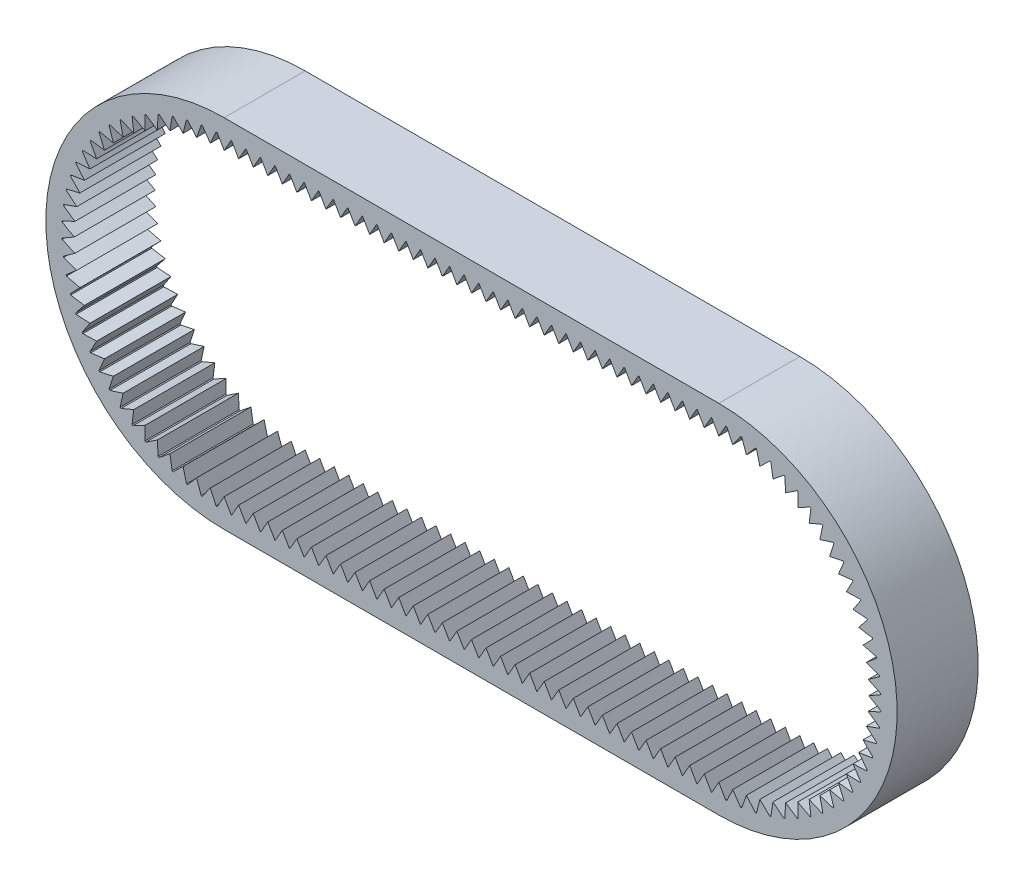
SolidWorks part; units mm, degrees
ref_plane "Front Plane" through (0, 0, 0) normal (0, 0, 1) x (1, 0, 0)
ref_plane "Top Plane" through (0, 0, 0) normal (0, 1, 0) x (1, 0, 0)
ref_plane "Right Plane" through (0, 0, 0) normal (1, 0, 0) x (0, 0, -1)
sketch "Sketch1" plane through (0, 0, 0) normal (0, 0, 1) x (1, 0, 0)
  line L0 (0.433, 10) -> (0.4646, 10)
  line L1 (0, 11) -> (30.5183, 11)
  line L2 (0, 9.25) -> (0.433, 10)
  line L4 (-0.4277, 9.9908) -> (0, 9.25)
  line L5 (30.0853, -10) -> (30.5183, -9.25)
  line L6 (0.8976, 9.25) -> (1.3306, 10)
  line L8 (0.4646, 10) -> (0.8976, 9.25)
  line L9 (1.7952, 9.25) -> (2.2282, 10)
  line L11 (1.3622, 10) -> (1.7952, 9.25)
  line L12 (2.6928, 9.25) -> (3.1258, 10)
  line L14 (2.2598, 10) -> (2.6928, 9.25)
  line L15 (3.5904, 9.25) -> (4.0234, 10)
  line L17 (3.1574, 10) -> (3.5904, 9.25)
  line L18 (4.488, 9.25) -> (4.921, 10)
  line L20 (4.055, 10) -> (4.488, 9.25)
  line L21 (5.3856, 9.25) -> (5.8186, 10)
  line L23 (4.9526, 10) -> (5.3856, 9.25)
  line L24 (6.2832, 9.25) -> (6.7162, 10)
  line L26 (5.8502, 10) -> (6.2832, 9.25)
  line L27 (7.1808, 9.25) -> (7.6138, 10)
  line L29 (6.7478, 10) -> (7.1808, 9.25)
  line L30 (8.0784, 9.25) -> (8.5114, 10)
  line L32 (7.6454, 10) -> (8.0784, 9.25)
  line L33 (8.976, 9.25) -> (9.409, 10)
  line L35 (8.543, 10) -> (8.976, 9.25)
  line L36 (9.8736, 9.25) -> (10.3066, 10)
  line L38 (9.4406, 10) -> (9.8736, 9.25)
  line L39 (10.7712, 9.25) -> (11.2042, 10)
  line L41 (10.3382, 10) -> (10.7712, 9.25)
  line L42 (11.6688, 9.25) -> (12.1018, 10)
  line L44 (11.2357, 10) -> (11.6688, 9.25)
  line L45 (12.5664, 9.25) -> (12.9994, 10)
  line L47 (12.1333, 10) -> (12.5664, 9.25)
  line L48 (13.464, 9.25) -> (13.897, 10)
  line L50 (13.0309, 10) -> (13.464, 9.25)
  line L51 (14.3616, 9.25) -> (14.7946, 10)
  line L53 (13.9285, 10) -> (14.3616, 9.25)
  line L54 (15.2591, 9.25) -> (15.6922, 10)
  line L56 (14.8261, 10) -> (15.2591, 9.25)
  line L57 (16.1567, 9.25) -> (16.5898, 10)
  line L59 (15.7237, 10) -> (16.1567, 9.25)
  line L60 (17.0543, 9.25) -> (17.4874, 10)
  line L62 (16.6213, 10) -> (17.0543, 9.25)
  line L63 (17.9519, 9.25) -> (18.385, 10)
  line L65 (17.5189, 10) -> (17.9519, 9.25)
  line L66 (18.8495, 9.25) -> (19.2825, 10)
  line L68 (18.4165, 10) -> (18.8495, 9.25)
  line L69 (19.7471, 9.25) -> (20.1801, 10)
  line L71 (19.3141, 10) -> (19.7471, 9.25)
  line L72 (20.6447, 9.25) -> (21.0777, 10)
  line L74 (20.2117, 10) -> (20.6447, 9.25)
  line L75 (21.5423, 9.25) -> (21.9753, 10)
  line L77 (21.1093, 10) -> (21.5423, 9.25)
  line L78 (22.4399, 9.25) -> (22.8729, 10)
  line L80 (22.0069, 10) -> (22.4399, 9.25)
  line L81 (23.3375, 9.25) -> (23.7705, 10)
  line L83 (22.9045, 10) -> (23.3375, 9.25)
  line L84 (24.2351, 9.25) -> (24.6681, 10)
  line L86 (23.8021, 10) -> (24.2351, 9.25)
  line L87 (25.1327, 9.25) -> (25.5657, 10)
  line L89 (24.6997, 10) -> (25.1327, 9.25)
  line L90 (26.0303, 9.25) -> (26.4633, 10)
  line L92 (25.5973, 10) -> (26.0303, 9.25)
  line L93 (26.9279, 9.25) -> (27.3609, 10)
  line L95 (26.4949, 10) -> (26.9279, 9.25)
  line L96 (27.8255, 9.25) -> (28.2585, 10)
  line L98 (27.3925, 10) -> (27.8255, 9.25)
  line L99 (28.7231, 9.25) -> (29.1561, 10)
  line L101 (28.2901, 10) -> (28.7231, 9.25)
  line L102 (29.6207, 9.25) -> (30.0537, 10)
  line L104 (29.1877, 10) -> (29.6207, 9.25)
  line L105 (30.5183, 9.25) -> (30.946, 9.9908)
  line L107 (30.0853, 10) -> (30.5183, 9.25)
  line L109 (-0.8535, 9.2105) -> (-0.4959, 9.9877)
  line L110 (30.5183, -9.25) -> (30.946, -9.9908)
  line L111 (29.1877, -10) -> (29.6207, -9.25)
  line L113 (29.6207, -9.25) -> (30.0537, -10)
  line L114 (28.2901, -10) -> (28.7231, -9.25)
  line L116 (28.7231, -9.25) -> (29.1561, -10)
  line L117 (27.3925, -10) -> (27.8255, -9.25)
  line L119 (27.8255, -9.25) -> (28.2585, -10)
  line L120 (26.4949, -10) -> (26.9279, -9.25)
  line L122 (26.9279, -9.25) -> (27.3609, -10)
  line L123 (25.5973, -10) -> (26.0303, -9.25)
  line L125 (26.0303, -9.25) -> (26.4633, -10)
  line L126 (24.6997, -10) -> (25.1327, -9.25)
  line L128 (25.1327, -9.25) -> (25.5657, -10)
  line L129 (23.8021, -10) -> (24.2351, -9.25)
  line L131 (24.2351, -9.25) -> (24.6681, -10)
  line L132 (22.9045, -10) -> (23.3375, -9.25)
  line L134 (23.3375, -9.25) -> (23.7705, -10)
  line L135 (22.0069, -10) -> (22.4399, -9.25)
  line L137 (22.4399, -9.25) -> (22.8729, -10)
  line L138 (21.1093, -10) -> (21.5423, -9.25)
  line L140 (21.5423, -9.25) -> (21.9753, -10)
  line L141 (20.2117, -10) -> (20.6447, -9.25)
  line L143 (20.6447, -9.25) -> (21.0777, -10)
  line L144 (19.3141, -10) -> (19.7471, -9.25)
  line L146 (19.7471, -9.25) -> (20.1801, -10)
  line L147 (18.4165, -10) -> (18.8495, -9.25)
  line L149 (18.8495, -9.25) -> (19.2825, -10)
  line L150 (17.5189, -10) -> (17.9519, -9.25)
  line L152 (17.9519, -9.25) -> (18.385, -10)
  line L153 (16.6213, -10) -> (17.0543, -9.25)
  line L155 (17.0543, -9.25) -> (17.4874, -10)
  line L156 (15.7237, -10) -> (16.1567, -9.25)
  line L158 (16.1567, -9.25) -> (16.5898, -10)
  line L159 (14.8261, -10) -> (15.2591, -9.25)
  line L161 (15.2591, -9.25) -> (15.6922, -10)
  line L162 (13.9285, -10) -> (14.3616, -9.25)
  line L164 (14.3616, -9.25) -> (14.7946, -10)
  line L165 (13.0309, -10) -> (13.464, -9.25)
  line L167 (13.464, -9.25) -> (13.897, -10)
  line L168 (12.1333, -10) -> (12.5664, -9.25)
  line L170 (12.5664, -9.25) -> (12.9994, -10)
  line L171 (11.2357, -10) -> (11.6688, -9.25)
  line L173 (11.6688, -9.25) -> (12.1018, -10)
  line L174 (10.3382, -10) -> (10.7712, -9.25)
  line L176 (10.7712, -9.25) -> (11.2042, -10)
  line L177 (9.4406, -10) -> (9.8736, -9.25)
  line L179 (9.8736, -9.25) -> (10.3066, -10)
  line L180 (8.543, -10) -> (8.976, -9.25)
  line L182 (8.976, -9.25) -> (9.409, -10)
  line L183 (7.6454, -10) -> (8.0784, -9.25)
  line L185 (8.0784, -9.25) -> (8.5114, -10)
  line L186 (6.7478, -10) -> (7.1808, -9.25)
  line L188 (7.1808, -9.25) -> (7.6138, -10)
  line L189 (5.8502, -10) -> (6.2832, -9.25)
  line L191 (6.2832, -9.25) -> (6.7162, -10)
  line L192 (4.9526, -10) -> (5.3856, -9.25)
  line L194 (5.3856, -9.25) -> (5.8186, -10)
  line L195 (4.055, -10) -> (4.488, -9.25)
  line L197 (4.488, -9.25) -> (4.921, -10)
  line L198 (3.1574, -10) -> (3.5904, -9.25)
  line L200 (3.5904, -9.25) -> (4.0234, -10)
  line L201 (2.2598, -10) -> (2.6928, -9.25)
  line L203 (2.6928, -9.25) -> (3.1258, -10)
  line L204 (1.3622, -10) -> (1.7952, -9.25)
  line L206 (1.7952, -9.25) -> (2.2282, -10)
  line L207 (0.4646, -10) -> (0.8976, -9.25)
  line L209 (0.8976, -9.25) -> (1.3306, -10)
  line L210 (-0.4277, -9.9908) -> (0, -9.25)
  line L212 (0, -9.25) -> (0.433, -10)
  line L214 (0.433, -10) -> (0.4646, -10)
  line L216 (-1.3477, 9.9088) -> (-0.8535, 9.2105)
  line L217 (-1.6997, 9.0925) -> (-1.4154, 9.8993)
  line L219 (-2.2563, 9.7421) -> (-1.6997, 9.0925)
  line L220 (-2.5314, 8.8969) -> (-2.3227, 9.7265)
  line L222 (-3.1455, 9.4924) -> (-2.5314, 8.8969)
  line L223 (-3.3415, 8.6254) -> (-3.2103, 9.4707)
  line L225 (-4.008, 9.1617) -> (-3.3415, 8.6254)
  line L226 (-4.1231, 8.2803) -> (-4.0704, 9.1341)
  line L228 (-4.8362, 8.7528) -> (-4.1231, 8.2803)
  line L229 (-4.8695, 7.8645) -> (-4.8958, 8.7196)
  line L231 (-5.6232, 8.2692) -> (-4.8695, 7.8645)
  line L232 (-5.5744, 7.3817) -> (-5.6795, 8.2306)
  line L234 (-6.3622, 7.7151) -> (-5.5744, 7.3817)
  line L235 (-6.2317, 6.8358) -> (-6.4147, 7.6715)
  line L237 (-7.0469, 7.0952) -> (-6.2317, 6.8358)
  line L238 (-6.8358, 6.2317) -> (-7.0952, 7.0469)
  line L240 (-7.6715, 6.4147) -> (-6.8358, 6.2317)
  line L241 (-7.3817, 5.5744) -> (-7.7151, 6.3622)
  line L243 (-8.2306, 5.6795) -> (-7.3817, 5.5744)
  line L244 (-7.8645, 4.8695) -> (-8.2692, 5.6232)
  line L246 (-8.7196, 4.8958) -> (-7.8645, 4.8695)
  line L247 (-8.2803, 4.1231) -> (-8.7528, 4.8362)
  line L249 (-9.1341, 4.0704) -> (-8.2803, 4.1231)
  line L250 (-8.6254, 3.3415) -> (-9.1617, 4.008)
  line L252 (-9.4707, 3.2103) -> (-8.6254, 3.3415)
  line L253 (-8.8969, 2.5314) -> (-9.4924, 3.1455)
  line L255 (-9.7265, 2.3227) -> (-8.8969, 2.5314)
  line L256 (-9.0925, 1.6997) -> (-9.7421, 2.2563)
  line L258 (-9.8993, 1.4154) -> (-9.0925, 1.6997)
  line L259 (-9.2105, 0.8535) -> (-9.9088, 1.3477)
  line L261 (-9.9877, 0.4959) -> (-9.2105, 0.8535)
  line L262 (-9.25, 0) -> (-9.9908, 0.4277)
  line L264 (-9.9908, -0.4277) -> (-9.25, 0)
  line L265 (-9.2105, -0.8535) -> (-9.9877, -0.4959)
  line L267 (-9.9088, -1.3477) -> (-9.2105, -0.8535)
  line L268 (-9.0925, -1.6997) -> (-9.8993, -1.4154)
  line L270 (-9.7421, -2.2563) -> (-9.0925, -1.6997)
  line L271 (-8.8969, -2.5314) -> (-9.7265, -2.3227)
  line L273 (-9.4924, -3.1455) -> (-8.8969, -2.5314)
  line L274 (-8.6254, -3.3415) -> (-9.4707, -3.2103)
  line L276 (-9.1617, -4.008) -> (-8.6254, -3.3415)
  line L277 (-8.2803, -4.1231) -> (-9.1341, -4.0704)
  line L279 (-8.7528, -4.8362) -> (-8.2803, -4.1231)
  line L280 (-7.8645, -4.8695) -> (-8.7196, -4.8958)
  line L282 (-8.2692, -5.6232) -> (-7.8645, -4.8695)
  line L283 (-7.3817, -5.5744) -> (-8.2306, -5.6795)
  line L285 (-7.7151, -6.3622) -> (-7.3817, -5.5744)
  line L286 (-6.8358, -6.2317) -> (-7.6715, -6.4147)
  line L288 (-7.0952, -7.0469) -> (-6.8358, -6.2317)
  line L289 (-6.2317, -6.8358) -> (-7.0469, -7.0952)
  line L291 (-6.4147, -7.6715) -> (-6.2317, -6.8358)
  line L292 (-5.5744, -7.3817) -> (-6.3622, -7.7151)
  line L294 (-5.6795, -8.2306) -> (-5.5744, -7.3817)
  line L295 (-4.8695, -7.8645) -> (-5.6232, -8.2692)
  line L297 (-4.8958, -8.7196) -> (-4.8695, -7.8645)
  line L298 (-4.1231, -8.2803) -> (-4.8362, -8.7528)
  line L300 (-4.0704, -9.1341) -> (-4.1231, -8.2803)
  line L301 (-3.3415, -8.6254) -> (-4.008, -9.1617)
  line L303 (-3.2103, -9.4707) -> (-3.3415, -8.6254)
  line L304 (-2.5314, -8.8969) -> (-3.1455, -9.4924)
  line L306 (-2.3227, -9.7265) -> (-2.5314, -8.8969)
  line L307 (-1.6997, -9.0925) -> (-2.2563, -9.7421)
  line L309 (-1.4154, -9.8993) -> (-1.6997, -9.0925)
  line L310 (-0.8535, -9.2105) -> (-1.3477, -9.9088)
  line L312 (-0.4959, -9.9877) -> (-0.8535, -9.2105)
  line L313 (0, -9.25) -> (-0.4277, -9.9908)
  line L315 (0.433, -10) -> (0, -9.25)
  line L316 (31.3718, 9.2105) -> (31.866, 9.9088)
  line L318 (31.0142, 9.9877) -> (31.3718, 9.2105)
  line L319 (32.218, 9.0925) -> (32.7746, 9.7421)
  line L321 (31.9337, 9.8993) -> (32.218, 9.0925)
  line L322 (33.0497, 8.8969) -> (33.6638, 9.4924)
  line L324 (32.841, 9.7265) -> (33.0497, 8.8969)
  line L325 (33.8598, 8.6254) -> (34.5263, 9.1617)
  line L327 (33.7286, 9.4707) -> (33.8598, 8.6254)
  line L328 (34.6414, 8.2803) -> (35.3545, 8.7528)
  line L330 (34.5887, 9.1341) -> (34.6414, 8.2803)
  line L331 (35.3878, 7.8645) -> (36.1415, 8.2692)
  line L333 (35.4141, 8.7196) -> (35.3878, 7.8645)
  line L334 (36.0927, 7.3817) -> (36.8805, 7.7151)
  line L336 (36.1978, 8.2306) -> (36.0927, 7.3817)
  line L337 (36.75, 6.8358) -> (37.5652, 7.0952)
  line L339 (36.933, 7.6715) -> (36.75, 6.8358)
  line L340 (37.3541, 6.2317) -> (38.1898, 6.4147)
  line L342 (37.6135, 7.0469) -> (37.3541, 6.2317)
  line L343 (37.9, 5.5744) -> (38.7489, 5.6795)
  line L345 (38.2334, 6.3622) -> (37.9, 5.5744)
  line L346 (38.3828, 4.8695) -> (39.2379, 4.8958)
  line L348 (38.7875, 5.6232) -> (38.3828, 4.8695)
  line L349 (38.7986, 4.1231) -> (39.6524, 4.0704)
  line L351 (39.2711, 4.8362) -> (38.7986, 4.1231)
  line L352 (39.1437, 3.3415) -> (39.989, 3.2103)
  line L354 (39.68, 4.008) -> (39.1437, 3.3415)
  line L355 (39.4152, 2.5314) -> (40.2448, 2.3227)
  line L357 (40.0107, 3.1455) -> (39.4152, 2.5314)
  line L358 (39.6108, 1.6997) -> (40.4176, 1.4154)
  line L360 (40.2604, 2.2563) -> (39.6108, 1.6997)
  line L361 (39.7288, 0.8535) -> (40.506, 0.4959)
  line L363 (40.4271, 1.3477) -> (39.7288, 0.8535)
  line L364 (39.7683, 0) -> (40.5091, -0.4277)
  line L366 (40.5091, 0.4277) -> (39.7683, 0)
  line L367 (39.7288, -0.8535) -> (40.4271, -1.3477)
  line L369 (40.506, -0.4959) -> (39.7288, -0.8535)
  line L370 (39.6108, -1.6997) -> (40.2604, -2.2563)
  line L372 (40.4176, -1.4154) -> (39.6108, -1.6997)
  line L373 (39.4152, -2.5314) -> (40.0107, -3.1455)
  line L375 (40.2448, -2.3227) -> (39.4152, -2.5314)
  line L376 (39.1437, -3.3415) -> (39.68, -4.008)
  line L378 (39.989, -3.2103) -> (39.1437, -3.3415)
  line L379 (38.7986, -4.1231) -> (39.2711, -4.8362)
  line L381 (39.6524, -4.0704) -> (38.7986, -4.1231)
  line L382 (38.3828, -4.8695) -> (38.7875, -5.6232)
  line L384 (39.2379, -4.8958) -> (38.3828, -4.8695)
  line L385 (37.9, -5.5744) -> (38.2334, -6.3622)
  line L387 (38.7489, -5.6795) -> (37.9, -5.5744)
  line L388 (37.3541, -6.2317) -> (37.6135, -7.0469)
  line L390 (38.1898, -6.4147) -> (37.3541, -6.2317)
  line L391 (36.75, -6.8358) -> (36.933, -7.6715)
  line L393 (37.5652, -7.0952) -> (36.75, -6.8358)
  line L394 (36.0927, -7.3817) -> (36.1978, -8.2306)
  line L396 (36.8805, -7.7151) -> (36.0927, -7.3817)
  line L397 (35.3878, -7.8645) -> (35.4141, -8.7196)
  line L399 (36.1415, -8.2692) -> (35.3878, -7.8645)
  line L400 (34.6414, -8.2803) -> (34.5887, -9.1341)
  line L402 (35.3545, -8.7528) -> (34.6414, -8.2803)
  line L403 (33.8598, -8.6254) -> (33.7286, -9.4707)
  line L405 (34.5263, -9.1617) -> (33.8598, -8.6254)
  line L406 (33.0497, -8.8969) -> (32.841, -9.7265)
  line L408 (33.6638, -9.4924) -> (33.0497, -8.8969)
  line L409 (32.218, -9.0925) -> (31.9337, -9.8993)
  line L411 (32.7746, -9.7421) -> (32.218, -9.0925)
  line L412 (31.3718, -9.2105) -> (31.0142, -9.9877)
  line L414 (31.866, -9.9088) -> (31.3718, -9.2105)
  line L415 (30.5183, -9.25) -> (30.0853, -10)
  line L417 (30.946, -9.9908) -> (30.5183, -9.25)
  line L484 (0, -11) -> (30.5183, -11)
  line L485 (1.3306, 10) -> (1.3622, 10)
  line L486 (0.433, 10) -> (0, 10) [skipped]
  line L487 (2.2282, 10) -> (2.2598, 10)
  line L488 (3.1258, 10) -> (3.1574, 10)
  line L489 (4.0234, 10) -> (4.055, 10)
  line L490 (4.921, 10) -> (4.9526, 10)
  line L491 (5.8186, 10) -> (5.8502, 10)
  line L492 (6.7162, 10) -> (6.7478, 10)
  line L493 (7.6138, 10) -> (7.6454, 10)
  line L494 (8.5114, 10) -> (8.543, 10)
  line L495 (9.409, 10) -> (9.4406, 10)
  line L496 (10.3066, 10) -> (10.3382, 10)
  line L497 (11.2042, 10) -> (11.2357, 10)
  line L498 (12.1018, 10) -> (12.1333, 10)
  line L499 (12.9994, 10) -> (13.0309, 10)
  line L500 (13.897, 10) -> (13.9285, 10)
  line L501 (14.7946, 10) -> (14.8261, 10)
  line L502 (15.6922, 10) -> (15.7237, 10)
  line L503 (16.5898, 10) -> (16.6213, 10)
  line L504 (17.4874, 10) -> (17.5189, 10)
  line L505 (18.385, 10) -> (18.4165, 10)
  line L506 (19.2825, 10) -> (19.3141, 10)
  line L507 (20.1801, 10) -> (20.2117, 10)
  line L508 (21.0777, 10) -> (21.1093, 10)
  line L509 (21.9753, 10) -> (22.0069, 10)
  line L510 (22.8729, 10) -> (22.9045, 10)
  line L511 (23.7705, 10) -> (23.8021, 10)
  line L512 (24.6681, 10) -> (24.6997, 10)
  line L513 (25.5657, 10) -> (25.5973, 10)
  line L514 (26.4633, 10) -> (26.4949, 10)
  line L515 (27.3609, 10) -> (27.3925, 10)
  line L516 (28.2585, 10) -> (28.2901, 10)
  line L517 (29.1561, 10) -> (29.1877, 10)
  line L518 (30.0537, 10) -> (30.0853, 10)
  line L519 (30.0537, -10) -> (30.0853, -10)
  line L520 (29.1561, -10) -> (29.1877, -10)
  line L521 (28.2585, -10) -> (28.2901, -10)
  line L522 (27.3609, -10) -> (27.3925, -10)
  line L523 (26.4633, -10) -> (26.4949, -10)
  line L524 (25.5657, -10) -> (25.5973, -10)
  line L525 (24.6681, -10) -> (24.6997, -10)
  line L526 (23.7705, -10) -> (23.8021, -10)
  line L527 (22.8729, -10) -> (22.9045, -10)
  line L528 (21.9753, -10) -> (22.0069, -10)
  line L529 (21.0777, -10) -> (21.1093, -10)
  line L530 (20.1801, -10) -> (20.2117, -10)
  line L531 (19.2825, -10) -> (19.3141, -10)
  line L532 (18.385, -10) -> (18.4165, -10)
  line L533 (17.4874, -10) -> (17.5189, -10)
  line L534 (16.5898, -10) -> (16.6213, -10)
  line L535 (14.7946, -10) -> (14.8261, -10)
  line L536 (15.6922, -10) -> (15.7237, -10)
  line L537 (13.897, -10) -> (13.9285, -10)
  line L538 (12.9994, -10) -> (13.0309, -10)
  line L539 (12.1018, -10) -> (12.1333, -10)
  line L540 (11.2042, -10) -> (11.2357, -10)
  line L541 (10.3066, -10) -> (10.3382, -10)
  line L542 (9.409, -10) -> (9.4406, -10)
  line L543 (8.5114, -10) -> (8.543, -10)
  line L544 (7.6138, -10) -> (7.6454, -10)
  line L545 (6.7162, -10) -> (6.7478, -10)
  line L546 (5.8186, -10) -> (5.8502, -10)
  line L547 (4.921, -10) -> (4.9526, -10)
  line L548 (4.0234, -10) -> (4.055, -10)
  line L549 (3.1258, -10) -> (3.1574, -10)
  line L550 (2.2282, -10) -> (2.2598, -10)
  line L551 (1.3306, -10) -> (1.3622, -10)
  arc A2 (-0.4277, 9.9908) -> (-0.4959, 9.9877) centre (0, 0) ccw
  arc A3 (-0.4959, -9.9877) -> (-0.4277, -9.9908) centre (0, 0) ccw
  arc A4 (30.946, -9.9908) -> (31.0142, -9.9877) centre (30.5183, 0) ccw
  arc A5 (0, 11) -> (0, -11) centre (0, 0) ccw
  arc A7 (31.0142, 9.9877) -> (30.946, 9.9908) centre (30.5183, 0) ccw
  arc A8 (31.9337, 9.8993) -> (31.866, 9.9088) centre (30.5183, 0) ccw
  arc A9 (30.5183, -11) -> (30.5183, 11) centre (30.5183, 0) ccw
  arc A10 (32.841, 9.7265) -> (32.7746, 9.7421) centre (30.5183, 0) ccw
  arc A11 (33.7286, 9.4707) -> (33.6638, 9.4924) centre (30.5183, 0) ccw
  arc A12 (34.5887, 9.1341) -> (34.5263, 9.1617) centre (30.5183, 0) ccw
  arc A13 (35.4141, 8.7196) -> (35.3545, 8.7528) centre (30.5183, 0) ccw
  arc A14 (36.1978, 8.2306) -> (36.1415, 8.2692) centre (30.5183, 0) ccw
  arc A15 (36.933, 7.6715) -> (36.8805, 7.7151) centre (30.5183, 0) ccw
  arc A16 (37.6135, 7.0469) -> (37.5652, 7.0952) centre (30.5183, 0) ccw
  arc A17 (38.2334, 6.3622) -> (38.1898, 6.4147) centre (30.5183, 0) ccw
  arc A18 (38.7875, 5.6232) -> (38.7489, 5.6795) centre (30.5183, 0) ccw
  arc A19 (39.2711, 4.8362) -> (39.2379, 4.8958) centre (30.5183, 0) ccw
  arc A20 (39.68, 4.008) -> (39.6524, 4.0704) centre (30.5183, 0) ccw
  arc A21 (40.0107, 3.1455) -> (39.989, 3.2103) centre (30.5183, 0) ccw
  arc A22 (40.2604, 2.2563) -> (40.2448, 2.3227) centre (30.5183, 0) ccw
  arc A23 (40.4271, 1.3477) -> (40.4176, 1.4154) centre (30.5183, 0) ccw
  arc A24 (40.5091, 0.4277) -> (40.506, 0.4959) centre (30.5183, 0) ccw
  arc A25 (40.506, -0.4959) -> (40.5091, -0.4277) centre (30.5183, 0) ccw
  arc A26 (40.4176, -1.4154) -> (40.4271, -1.3477) centre (30.5183, 0) ccw
  arc A27 (40.2448, -2.3227) -> (40.2604, -2.2563) centre (30.5183, 0) ccw
  arc A28 (39.989, -3.2103) -> (40.0107, -3.1455) centre (30.5183, 0) ccw
  arc A29 (39.6524, -4.0704) -> (39.68, -4.008) centre (30.5183, 0) ccw
  arc A30 (39.2379, -4.8958) -> (39.2711, -4.8362) centre (30.5183, 0) ccw
  arc A31 (38.7489, -5.6795) -> (38.7875, -5.6232) centre (30.5183, 0) ccw
  arc A32 (38.1898, -6.4147) -> (38.2334, -6.3622) centre (30.5183, 0) ccw
  arc A33 (37.5652, -7.0952) -> (37.6135, -7.0469) centre (30.5183, 0) ccw
  arc A34 (36.8805, -7.7151) -> (36.933, -7.6715) centre (30.5183, 0) ccw
  arc A35 (36.1415, -8.2692) -> (36.1978, -8.2306) centre (30.5183, 0) ccw
  arc A36 (35.3545, -8.7528) -> (35.4141, -8.7196) centre (30.5183, 0) ccw
  arc A37 (34.5263, -9.1617) -> (34.5887, -9.1341) centre (30.5183, 0) ccw
  arc A38 (33.6638, -9.4924) -> (33.7286, -9.4707) centre (30.5183, 0) ccw
  arc A39 (32.7746, -9.7421) -> (32.841, -9.7265) centre (30.5183, 0) ccw
  arc A40 (31.866, -9.9088) -> (31.9337, -9.8993) centre (30.5183, 0) ccw
  arc A41 (-1.4154, -9.8993) -> (-1.3477, -9.9088) centre (0, 0) ccw
  arc A42 (-2.3227, -9.7265) -> (-2.2563, -9.7421) centre (0, 0) ccw
  arc A43 (-3.2103, -9.4707) -> (-3.1455, -9.4924) centre (0, 0) ccw
  arc A44 (-4.0704, -9.1341) -> (-4.008, -9.1617) centre (0, 0) ccw
  arc A45 (-4.8958, -8.7196) -> (-4.8362, -8.7528) centre (0, 0) ccw
  arc A46 (-5.6795, -8.2306) -> (-5.6232, -8.2692) centre (0, 0) ccw
  arc A47 (-6.4147, -7.6715) -> (-6.3622, -7.7151) centre (0, 0) ccw
  arc A48 (-7.0952, -7.0469) -> (-7.0469, -7.0952) centre (0, 0) ccw
  arc A49 (-7.7151, -6.3622) -> (-7.6715, -6.4147) centre (0, 0) ccw
  arc A50 (-8.2692, -5.6232) -> (-8.2306, -5.6795) centre (0, 0) ccw
  arc A51 (-8.7528, -4.8362) -> (-8.7196, -4.8958) centre (0, 0) ccw
  arc A52 (-9.1617, -4.008) -> (-9.1341, -4.0704) centre (0, 0) ccw
  arc A53 (-9.4924, -3.1455) -> (-9.4707, -3.2103) centre (0, 0) ccw
  arc A54 (-9.7421, -2.2563) -> (-9.7265, -2.3227) centre (0, 0) ccw
  arc A55 (-9.9088, -1.3477) -> (-9.8993, -1.4154) centre (0, 0) ccw
  arc A56 (-9.9908, -0.4277) -> (-9.9877, -0.4959) centre (0, 0) ccw
  arc A57 (-9.9877, 0.4959) -> (-9.9908, 0.4277) centre (0, 0) ccw
  arc A58 (-9.8993, 1.4154) -> (-9.9088, 1.3477) centre (0, 0) ccw
  arc A59 (-9.7265, 2.3227) -> (-9.7421, 2.2563) centre (0, 0) ccw
  arc A60 (-9.4707, 3.2103) -> (-9.4924, 3.1455) centre (0, 0) ccw
  arc A61 (-9.1341, 4.0704) -> (-9.1617, 4.008) centre (0, 0) ccw
  arc A62 (-8.7196, 4.8958) -> (-8.7528, 4.8362) centre (0, 0) ccw
  arc A63 (-8.2306, 5.6795) -> (-8.2692, 5.6232) centre (0, 0) ccw
  arc A64 (-7.6715, 6.4147) -> (-7.7151, 6.3622) centre (0, 0) ccw
  arc A65 (-7.0469, 7.0952) -> (-7.0952, 7.0469) centre (0, 0) ccw
  arc A66 (-6.3622, 7.7151) -> (-6.4147, 7.6715) centre (0, 0) ccw
  arc A67 (-5.6232, 8.2692) -> (-5.6795, 8.2306) centre (0, 0) ccw
  arc A68 (-4.8362, 8.7528) -> (-4.8958, 8.7196) centre (0, 0) ccw
  arc A69 (-4.008, 9.1617) -> (-4.0704, 9.1341) centre (0, 0) ccw
  arc A70 (-3.1455, 9.4924) -> (-3.2103, 9.4707) centre (0, 0) ccw
  arc A71 (-2.2563, 9.7421) -> (-2.3227, 9.7265) centre (0, 0) ccw
  arc A72 (-1.3477, 9.9088) -> (-1.4154, 9.8993) centre (0, 0) ccw
  point P327 (0, 0)
  point P431 (30.5183, 0)
  dimension "D1" = 35
  dimension "D2" = 35
  dimension "D3" = 35
extrude "Boss-Extrude1" add sketch "Sketch1" along normal blind 5 contours L484 A9 L1 A5 A72 L216 L109 A2 L4 L2 L0 L8 L6 L485 L11 L9 L487 L14 L12 L488 L17 L15 L489 L20 L18 L490 L23 L21 L491 L26 L24 L492 L29 L27 L493 L32 L30 L494 L35 L33 L495 L38 L36 L496 L41 L39 L497 L44 L42 L498
